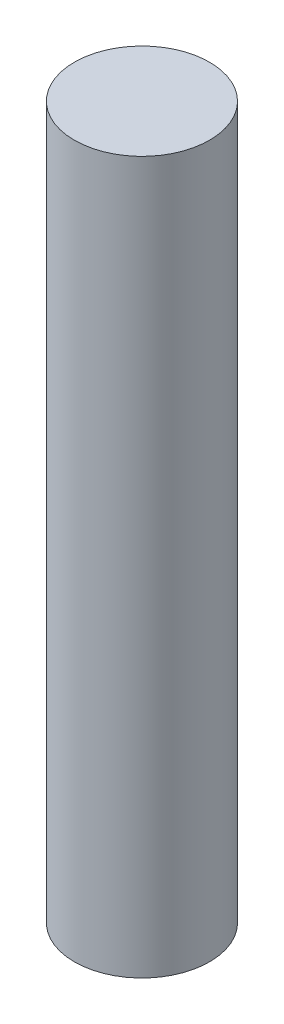
SolidWorks part; units mm, degrees
ref_plane "Front Plane" through (0, 0, 0) normal (0, 0, 1) x (1, 0, 0)
ref_plane "Top Plane" through (0, 0, 0) normal (0, 1, 0) x (1, 0, 0)
ref_plane "Right Plane" through (0, 0, 0) normal (1, 0, 0) x (0, 0, -1)
sketch "Sketch1" plane through (0, 0, 0) normal (0, 1, 0) x (1, 0, 0)
  circle A0 centre (0, 0) radius 2.85
  dimension "D1" = 5.7
extrude "Boss-Extrude1" add sketch "Sketch1" along normal blind 30
